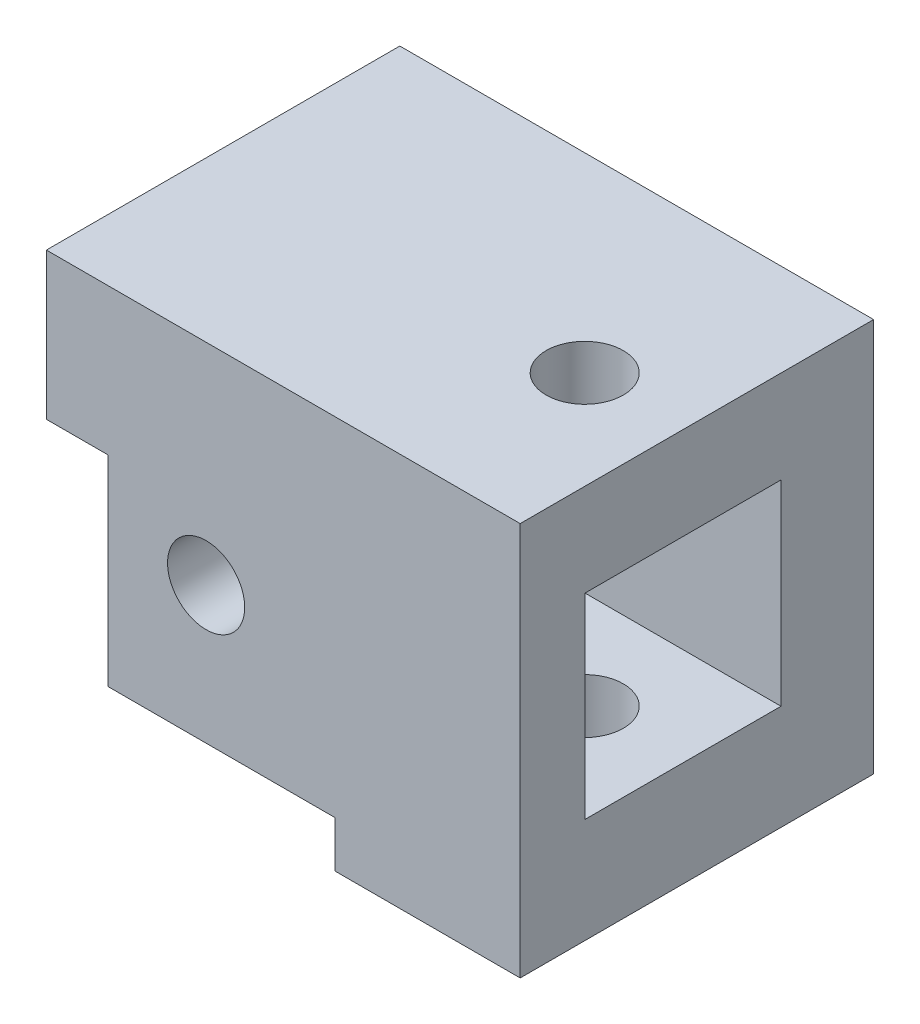
SolidWorks part; units mm, degrees
other "标注1"
sketch "草图10" plane through (-12.7, -9.75, -8.45) normal (-0.1098, -0.1078, -0.9881) x (-0.9937, -0.0091, 0.1114)
material "ABS"
ref_plane "Front Plane" through (0, 0, 0) normal (0, 0, 1) x (1, 0, 0)
ref_plane "Top Plane" through (0, 0, 0) normal (0, 1, 0) x (1, 0, 0)
ref_plane "Right Plane" through (0, 0, 0) normal (1, 0, 0) x (0, 0, -1)
sketch "Sketch1" plane through (0, 0, 0) normal (1, 0, 0) x (0, 0, -1)
  line L1 (-8.45, -12) -> (8.45, -12)
  line L2 (-8.45, -12) -> (-8.45, 12)
  line L3 (-8.45, 12) -> (8.45, 12)
  line L4 (8.45, -12) -> (8.45, 12)
  line L5 (-8.45, -12) -> (8.45, 12) construction
  line L6 (-8.45, 12) -> (8.45, -12) construction
  point P0 (0, 0)
  dimension "D1" = 16.9
  dimension "D2" = 24
extrude "Boss-Extrude1" add sketch "Sketch1" along normal blind 17
sketch "Sketch2" plane through (17, 0, 0) normal (1, 0, 0) x (0, 0, -1)
  line L0 (8.45, -12) -> (8.45, 12) construction
  line L1 (8.45, 6) -> (-4.25, 6)
  line L2 (8.45, 6) -> (8.45, -6.7)
  line L3 (8.45, -6.7) -> (-4.25, -6.7)
  line L4 (-4.25, 6) -> (-4.25, -6.7)
  line L5 (8.45, 12) -> (-8.45, 12) construction
  line L6 (-8.45, -12) -> (8.45, -12) construction
  dimension "D1" = 6
  dimension "D2" = 5.3
  dimension "D3" = 12.7
extrude "Cut-Extrude1" cut sketch "Sketch2" against normal through all
sketch "Sketch3" plane through (0, 12, 0) normal (0, 1, 0) x (1, 0, 0)
  line L0 (17, 2.1) -> (0, 2.1) construction
  line L1 (17, 8.45) -> (17, -8.45) construction
  line L2 (0, 8.45) -> (0, -8.45) construction
  line L4 (0, -4.25) -> (17, -4.25) construction
  circle A0 centre (7.63, 2.1) radius 2.5
  dimension "D2" = 7.63
  dimension "D3" = 5
  dimension "D1" = 6.35
extrude "Cut-Extrude2" cut sketch "Sketch3" against normal through all
sketch "Sketch4" plane through (0, 0, 0) normal (-1, 0, 0) x (0, 0, 1)
  line L0 (-8.45, 12) -> (-8.45, 6)
  line L1 (-8.45, 6) -> (4.25, 6)
  line L2 (4.25, 6) -> (4.25, -12)
  line L3 (8.45, -12) -> (-8.45, -12) construction
  line L4 (4.25, -12) -> (8.45, -12)
  line L5 (8.45, -12) -> (8.45, 12)
  line L6 (8.45, 12) -> (-8.45, 12)
extrude "Boss-Extrude2" add sketch "Sketch4" along normal blind 12.7
sketch "草图1" plane through (0, 0, -8.45) normal (0, 0, -1) x (-1, 0, 0)
  line L0 (-17, -12) -> (0, -12) construction
  line L9 (12.7, 12) -> (0, 12)
  line L10 (12.7, 12) -> (12.7, -12)
  line L11 (12.7, -12) -> (1.2749, -12)
  line L15 (0, 0.5) -> (0, 12)
  line L17 (1.2749, -12) -> (-11.4454, -12)
  line L18 (-11.4454, -12) -> (0, 0.5)
  dimension "D1" = 12.7
  dimension "D2" = 11.5
  dimension "D3" = 12.7203
  dimension "D4" = 16.9483
sketch "草图3" plane through (-12.7, 0, 0) normal (-1, 0, 0) x (0, 0, 1)
  line L0 (8.45, 12) -> (-7.55, 12)
  line L1 (8.45, 12) -> (-8.45, 12) construction
  line L2 (-7.55, 12) -> (8.45, -5)
  line L3 (8.45, -12) -> (8.45, 12) construction
  line L4 (8.45, -5) -> (8.45, 12)
  dimension "D1" = 16
  dimension "D2" = 17
extrude "凸台-拉伸3" add sketch "草图3" along normal blind 4
extrude "凸台-拉伸4" add sketch "草图1" along normal blind 4
sketch "Sketch5" plane through (0, 0, 8.45) normal (0, 0, 1) x (1, 0, 0)
  line L0 (-6.35, 12) -> (-6.35, -12) construction
  line L1 (17, 12) -> (-16.7, 12) construction
  line L2 (17, -12) -> (-12.7, -12) construction
  line L3 (-12.7, -12) -> (-12.7, -5) construction
  line L4 (-12.7, 6) -> (17, 6) construction
  circle A0 centre (-6.35, -1.63) radius 2.5
  dimension "D2" = 7.63
  dimension "D3" = 5
  dimension "D1" = 6.35
extrude "Cut-Extrude3" cut sketch "Sketch5" against normal through all
sketch "草图4" plane through (0, 12, 0) normal (0, 1, 0) x (1, 0, 0)
  line L0 (17, 8.45) -> (0, 8.45) construction
  line L1 (17, -8.45) -> (14, -8.45)
  line L2 (17, -8.45) -> (17, 8.45)
  line L3 (17, 8.45) -> (14, 8.45)
  line L4 (14, -8.45) -> (14, 8.45)
  dimension "D1" = 3
extrude "切除-拉伸1" cut sketch "草图4" against normal through all
sketch "草图5" plane through (0, 0, 8.45) normal (0, 0, 1) x (1, 0, 0)
  line L6 (-12.7, -12) -> (0, -12)
  line L7 (-12.7, -12) -> (-12.7, -10.5)
  line L8 (-12.7, -10.5) -> (0, -10.5)
  line L9 (0, -12) -> (0, -10.5)
  dimension "D1" = 12.7
  dimension "D2" = 1.5
extrude "切除-拉伸2" cut sketch "草图5" against normal through all
sketch "Sketch7" plane through (0, 0, 0) normal (-1, 0, 0) x (0, 0, 1)
  line L0 (-12.45, -12) -> (-12.45, -10.5)
  line L1 (-12.45, -10.5) -> (-8.45, -10.5)
  line L2 (-8.45, -10.5) -> (-8.45, -6.7)
  line L3 (-8.45, -10.5) -> (-8.45, 6) construction
  line L4 (4.25, -6.7) -> (-8.45, -6.7) construction
  line L5 (4.25, -6.7) -> (4.25, -10.5)
  line L6 (4.25, -10.5) -> (8.45, -10.5)
  line L7 (8.45, -10.5) -> (8.45, -12)
  line L8 (8.45, -12) -> (-12.45, -12)
  line M8 (-8.45, -6.7) -> (-8.45, -10.5)
  line M9 (-8.45, -10.5) -> (-12.45, -10.5)
  line M10 (-12.45, -10.5) -> (-12.45, -12)
  line M11 (-12.45, -12) -> (8.45, -12)
  line M12 (8.45, -12) -> (8.45, -10.5)
  line M13 (8.45, -10.5) -> (4.25, -10.5)
  line M14 (4.25, -10.5) -> (4.25, -6.7)
  line M15 (4.25, -6.7) -> (-8.45, -6.7)
extrude "Cut-Extrude4" cut sketch "Sketch7" against normal blind 2 and the other way through all contours M15 M8 M9 M10 M11 M12 M13 M14
sketch "草图6" plane through (0, 0, 0) normal (1, 0, 0) x (0, 0, -1)
  line L1 (8.45, 12) -> (12.45, 12)
  line L2 (8.45, 12) -> (8.45, -12)
  line L3 (8.45, -12) -> (12.45, -12)
  line L4 (12.45, 12) -> (12.45, -12)
extrude "切除-拉伸3" cut sketch "草图6" against normal through all
sketch "草图7" plane through (2, 0, 0) normal (-1, 0, 0) x (0, 0, 1)
  line L1 (-12.45, -10.5) -> (8.45, -10.5)
  line L2 (-12.45, -10.5) -> (-12.45, -12)
  line L3 (-12.45, -12) -> (8.45, -12)
  line L4 (8.45, -10.5) -> (8.45, -12)
extrude "切除-拉伸4" cut sketch "草图7" against normal through all
sketch "草图8" plane through (14, 0, 0) normal (1, 0, 0) x (0, 0, -1)
  line L1 (8.45, 12) -> (12.45, 12)
  line L2 (8.45, 12) -> (8.45, -10.5)
  line L3 (8.45, -10.5) -> (12.45, -10.5)
  line L4 (12.45, 12) -> (12.45, -10.5)
extrude "切除-拉伸5" cut sketch "草图8" against normal through all
sketch "草图9" plane through (0, 0, -8.45) normal (0, 0, -1) x (-1, 0, 0)
  line L1 (12.7, 12) -> (16.7, 12)
  line L2 (12.7, 12) -> (12.7, -5)
  line L3 (12.7, -5) -> (16.7, -5)
  line L4 (16.7, 12) -> (16.7, -5)
extrude "切除-拉伸6" cut sketch "草图9" against normal through all
sketch "草图11" plane through (2, 0, 0) normal (-1, 0, 0) x (0, 0, 1)
  line L2 (4.25, -6.7) -> (-8.45, -6.7)
  line L3 (4.25, -6.7) -> (4.25, -10.5)
  line L4 (4.25, -10.5) -> (-8.45, -10.5)
  line L5 (-8.45, -6.7) -> (-8.45, -10.5)
extrude "凸台-拉伸5" add sketch "草图11" along normal blind 2
sketch "草图12" plane through (14, 0, 0) normal (1, 0, 0) x (0, 0, -1)
  line L0 (-8.45, -10.5) -> (8.45, -10.5) construction
  line L1 (8.45, 12) -> (14.45, 12)
  line L2 (8.45, 12) -> (8.45, -10.5)
  line L3 (8.45, -10.5) -> (14.45, -10.5)
  line L4 (14.45, 12) -> (14.45, -10.5)
  dimension "D1" = 6
extrude "凸台-拉伸6" add sketch "草图12" against normal up to surface (26.7 mm away) up to face at (-12.7, 2.5, 1.4167)
sketch "草图21" plane through (-12.7, 0, 0) normal (-1, 0, 0) x (0, 0, 1)
  line L0 (-14.45, 12) -> (8.45, 12)
  line L1 (8.45, 12) -> (8.45, 2.5)
  line L2 (8.45, -10.5) -> (8.45, 12) construction
  line L3 (8.45, 2.5) -> (-14.45, 2.5)
  line L4 (-14.45, -10.5) -> (-14.45, 12) construction
  line L5 (-14.45, 2.5) -> (-14.45, 12)
  line L6 (-8.45, 6) -> (4.25, 6) construction
  dimension "D1" = 3.5
extrude "凸台-拉伸7" add sketch "草图21" along normal blind 4
sketch "草图14" plane through (0, 0, 8.45) normal (0, 0, 1) x (1, 0, 0)
  circle A0 centre (-6.35, -1.63) radius 2.5
extrude "切除-拉伸7" cut sketch "草图14" against normal through all
sketch "草图22" plane through (0, -10.5, 0) normal (0, -1, 0) x (1, 0, 0)
  line L0 (-12.7, -14.45) -> (14, -14.45) construction
  line L1 (14, 8.45) -> (2, 8.45)
  line L2 (14, 8.45) -> (14, -14.45)
  line L3 (14, -14.45) -> (2, -14.45)
  line L4 (2, 8.45) -> (2, -14.45)
  circle A0 centre (7.63, -2.1) radius 2.5
  point P7 (7.63, -2.1)
  dimension "D2" = 5
  dimension "D1" = 12
extrude "凸台-拉伸8" add sketch "草图22" along normal blind 3
